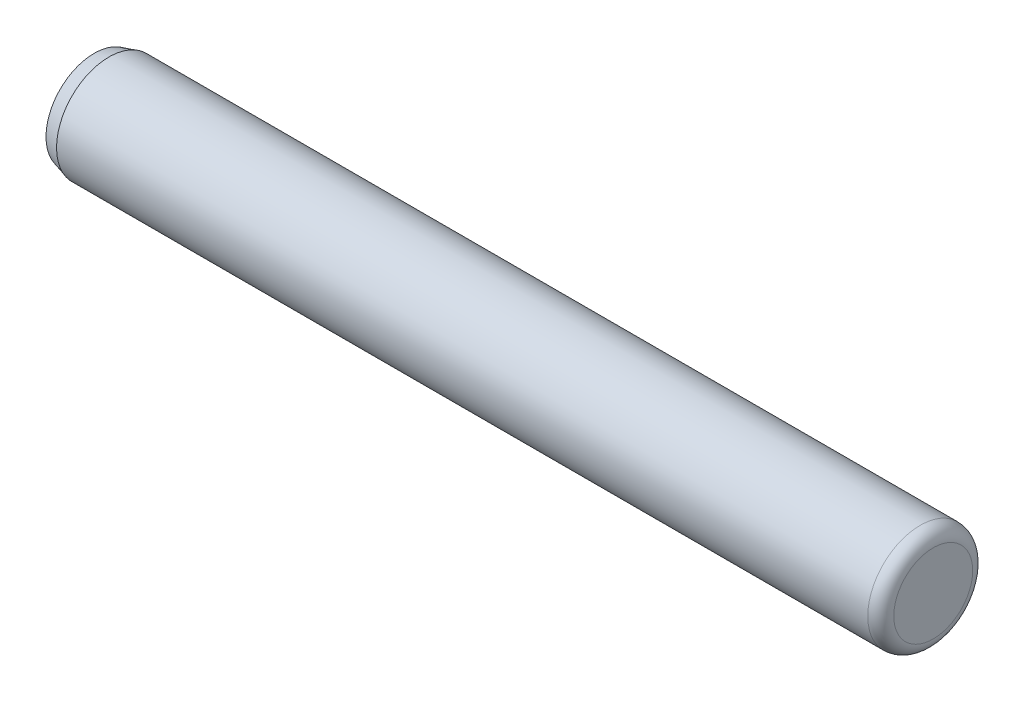
SolidWorks part; units mm, degrees
ref_plane "Front" through (0, 0, 0) normal (0, 0, 1) x (1, 0, 0)
ref_plane "Top" through (0, 0, 0) normal (0, 1, 0) x (1, 0, 0)
ref_plane "Right" through (0, 0, 0) normal (1, 0, 0) x (0, 0, -1)
sketch "Sketch1" plane through (0, 0, 0) normal (1, 0, 0) x (0, 0, -1)
  circle A0 centre (0, 0) radius 3.1775 construction
  point P3 (0, 3.1775)
  dimension "Diameter" = 6.3551
sketch "Sketch2" plane through (0, 0, 0) normal (0, 0, 1) x (1, 0, 0)
  line L0 (-25.4, 0) -> (25.4, 0) construction
  line L1 (25.4, 2.3901) -> (25.4, -0.6481) construction
  line L2 (-25.4, 2.921) -> (-25.4, -2.921) construction
  line L3 (-25.4, 2.921) -> (-25.4, 3.1775) construction
  line L4 (-25.4, -2.921) -> (-25.4, -3.1775) construction
  line L5 (-25.4, 2.921) -> (-24.5053, 3.1775) construction
  line L6 (-24.5053, 3.1775) -> (24.6126, 3.1775) construction
  arc A0 (24.6126, 3.1775) -> (25.4, 2.3901) centre (24.6126, 2.3901) cw construction
  point P6 (-19.0449, 0)
  point P8 (19.0449, 0)
  point P23 (23.2918, 3.1775)
  dimension "Crown Radius" = 0.7874
  dimension "Length" = 50.8
  dimension "D1" = 6.3551
  dimension "D2" = 6.3551
  dimension "Point Diameter" = 5.842
  dimension "D3" = 16
  dimension "Crown Height" = 2.1082
sketch "Sketch3" plane through (0, 0, 0) normal (0, 0, 1) x (1, 0, 0)
  line L0 (25.4, 2.3901) -> (25.4, -0.6481) construction
  line L1 (-24.5053, 3.1775) -> (24.6126, 3.1775) construction
  line L2 (-25.4, 2.921) -> (-24.5053, 3.1775) construction
  line L3 (-25.4, 2.921) -> (-25.4, -2.921) construction
  line L4 (-25.4, 0) -> (25.4, 0) construction
  line L5 (25.4, 2.3901) -> (25.4, 0)
  line L6 (-24.5053, 3.1775) -> (24.6126, 3.1775)
  line L7 (-25.4, 2.921) -> (-24.5053, 3.1775)
  line L8 (-25.4, 2.921) -> (-25.4, 0)
  line L9 (-25.4, 0) -> (25.4, 0)
  arc A0 (25.4, 2.3901) -> (24.6126, 3.1775) centre (24.6126, 2.3901) ccw construction
  arc A1 (25.4, 2.3901) -> (24.6126, 3.1775) centre (24.6126, 2.3901) ccw
revolve "Revolve1" add sketch "Sketch3" angle 360 about L0
equation "\"D1@Sketch2\" = \"Diameter@Sketch1\""
equation "\"D2@Sketch2\" = \"Diameter@Sketch1\""
